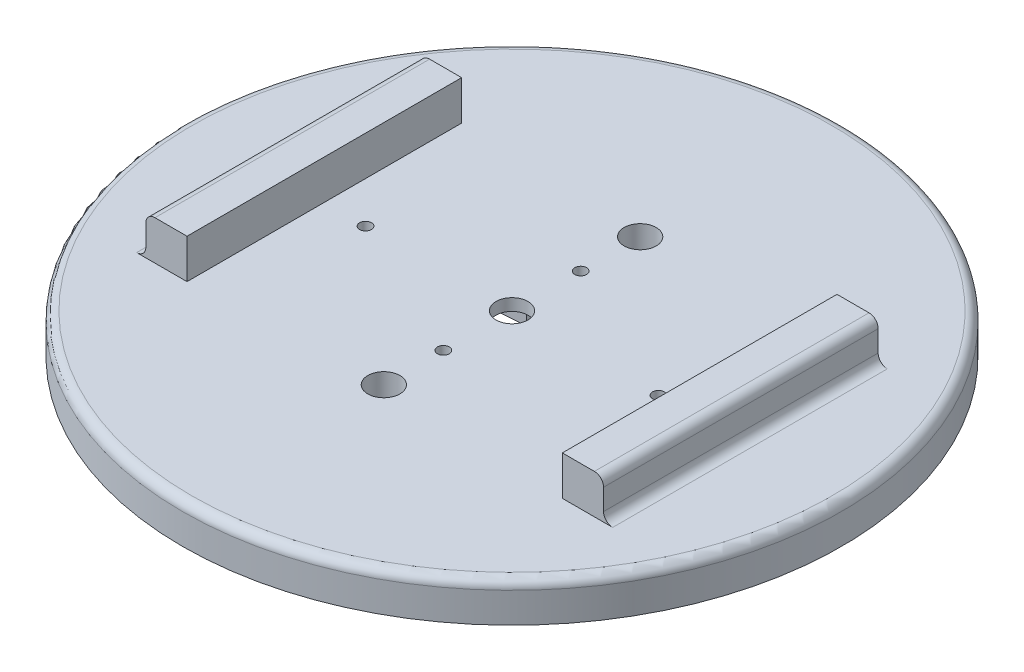
SolidWorks part; units mm, degrees
ref_plane "Alzado" through (0, 0, 0) normal (0, 0, 1) x (1, 0, 0)
ref_plane "Planta" through (0, 0, 0) normal (0, 1, 0) x (1, 0, 0)
ref_plane "Vista lateral" through (0, 0, 0) normal (1, 0, 0) x (0, 0, -1)
sketch "Croquis1" plane through (0, 0, 0) normal (0, 1, 0) x (1, 0, 0)
  circle A0 centre (0, 0) radius 36
  circle A1 centre (0, 14) radius 1.75
  circle A2 centre (0, -14) radius 1.75
  dimension "D1" = 72
  dimension "D2" = 3.5
  dimension "D3" = 3.5
  dimension "D4" = 14
  dimension "D5" = 14
extrude "Saliente-Extruir1" add sketch "Croquis1" along normal blind 4.3
sketch "Croquis2" plane through (0, 4.3, 0) normal (0, 1, 0) x (1, 0, 0)
  line L0 (0, 0) -> (20.5, 0) construction
  line L1 (25, 15) -> (20.5, 15)
  line L2 (25, 15) -> (25, -15)
  line L3 (25, -15) -> (20.5, -15)
  line L4 (20.5, 15) -> (20.5, -15)
  line L5 (0, 4.7684) -> (0, -4.0428) construction
  line L6 (-20.5, 15) -> (-20.5, -15)
  line L7 (-25, -15) -> (-20.5, -15)
  line L8 (-25, 15) -> (-25, -15)
  line L9 (-25, 15) -> (-20.5, 15)
  dimension "D1" = 30
  dimension "D2" = 4.5
  dimension "D3" = 20.5
extrude "Saliente-Extruir2" add sketch "Croquis2" along normal blind 4.3
fillet "Redondeo1" radius 1 5 edges at (0, 4.3, 36) (-25, 4.3, 0) (-25, 8.6, 0) (25, 4.3, 0) (25, 8.6, 0)
sketch "Croquis3" plane through (0, 0, 0) normal (0, -1, 0) x (1, 0, 0)
  line L0 (0, 4.9758) -> (0, -4.5611) construction
  line L1 (2.1, 3.6597) -> (16.8, 2.5)
  line L2 (-16.8, 0) -> (16.8, 0) construction
  line L3 (16.8, -2.5) -> (2.1, -3.6597)
  line L4 (-16.8, -2.5) -> (-2.1, -3.6597)
  line L5 (-2.1, 3.6597) -> (-16.8, 2.5)
  line L6 (0, 7.65) -> (0, -7.65) construction
  line L7 (2.1, 7.65) -> (2.1, 3.6597)
  line L8 (-2.1, 7.65) -> (-2.1, 3.6597)
  line L9 (2.1, -3.6597) -> (2.1, -7.65)
  line L10 (-2.1, -3.6597) -> (-2.1, -7.65)
  arc A0 (16.8, -2.5) -> (16.8, 2.5) centre (16.8, 0) ccw
  arc A3 (-16.8, -2.5) -> (-16.8, 2.5) centre (-16.8, 0) cw
  arc A4 (2.1, 7.65) -> (-2.1, 7.65) centre (0, 7.65) ccw
  arc A5 (-2.1, -7.65) -> (2.1, -7.65) centre (0, -7.65) ccw
  point P12 (0, 0)
  point P22 (0, 9.75)
  point P23 (0, -9.75)
  dimension "D1" = 2.1
  dimension "D4" = 4.2
  dimension "D5" = 19.5
extrude "Cortar-Extruir1" cut sketch "Croquis3" against normal blind 3
sketch "Croquis4" plane through (0, 0, 0) normal (0, -1, 0) x (1, 0, 0)
  circle A0 centre (0, 0) radius 1.75
  dimension "D1" = 3.5
extrude "Cortar-Extruir2" cut sketch "Croquis4" against normal blind 10
sketch "Croquis5" plane through (0, 0, 0) normal (0, -1, 0) x (1, 0, 0)
  line L0 (16, 0) -> (-16, 0) construction
  line L1 (0, 7.5) -> (0, -7.5) construction
  circle A0 centre (16, 0) radius 0.65
  circle A1 centre (-16, 0) radius 0.65
  circle A3 centre (0, 7.5) radius 0.65
  circle A4 centre (0, -7.5) radius 0.65
  point P3 (0, 0)
  point P8 (0, 0)
  dimension "D2" = 1.3
  dimension "D3" = 1.3
  dimension "D5" = 1.3
  dimension "D6" = 1.3
  dimension "D1" = 32
  dimension "D4" = 15
extrude "Cortar-Extruir3" cut sketch "Croquis5" against normal blind 10
